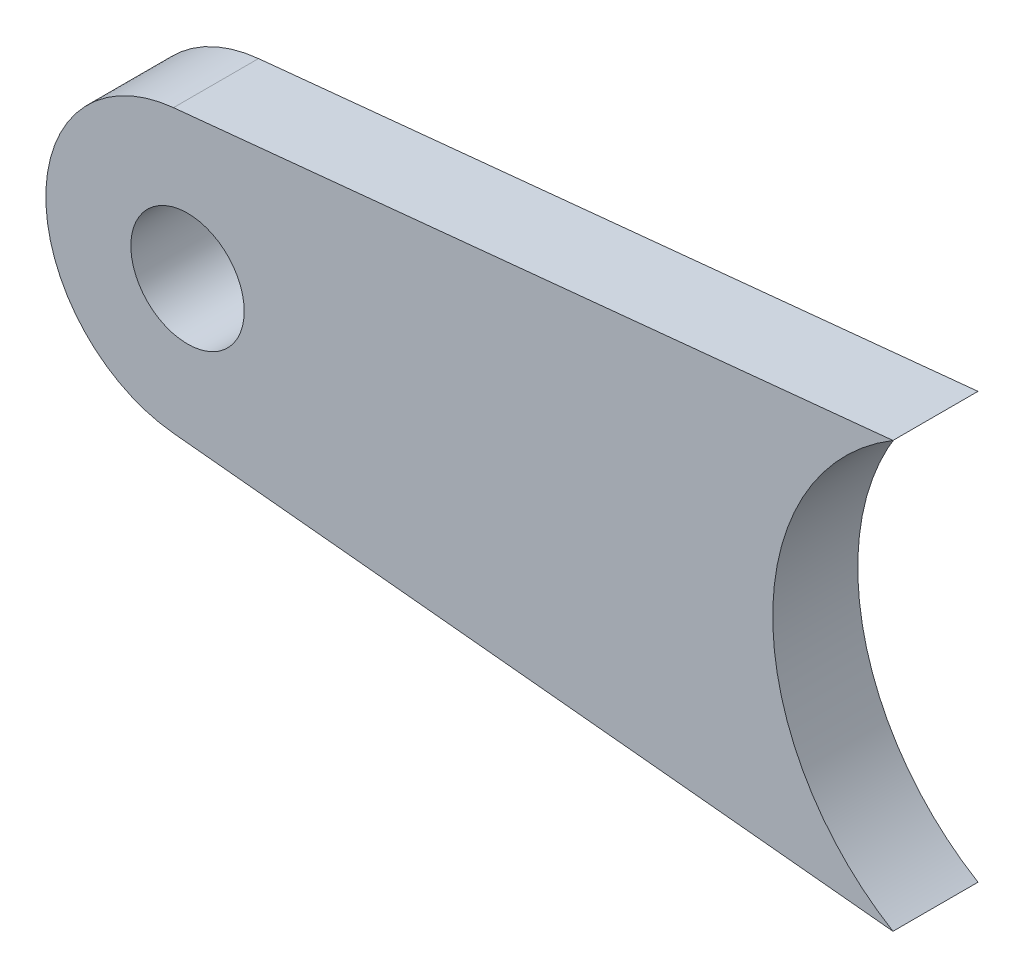
SolidWorks part; units mm, degrees
material "ASTM A36 Steel"
ref_plane "Front Plane" through (0, 0, 0) normal (0, 0, 1) x (1, 0, 0)
ref_plane "Top Plane" through (0, 0, 0) normal (0, 1, 0) x (1, 0, 0)
ref_plane "Right Plane" through (0, 0, 0) normal (1, 0, 0) x (0, 0, -1)
sketch "Sketch2" plane through (0, 0, 0) normal (0, 0, 1) x (1, 0, 0)
  line L0 (59.7872, 30) -> (-41.764, 19.9018)
  line L1 (-41.764, -19.9018) -> (59.7872, -30)
  arc A0 (-41.764, 19.9018) -> (-41.764, -19.9018) centre (-39.785, 0) ccw
  arc A1 (59.7872, 30) -> (59.7872, -30) centre (77.815, 0) ccw
  circle A2 centre (-39.785, 0) radius 8
  dimension "D1" = 20
  dimension "D2" = 35
  dimension "D6" = 119.5722
  dimension "D7" = 16
  dimension "D3" = 102.0521
  dimension "D4" = 102.0521
  dimension "D5" = 59.785
extrude "Boss-Extrude1" add sketch "Sketch2" along normal mid plane 12
